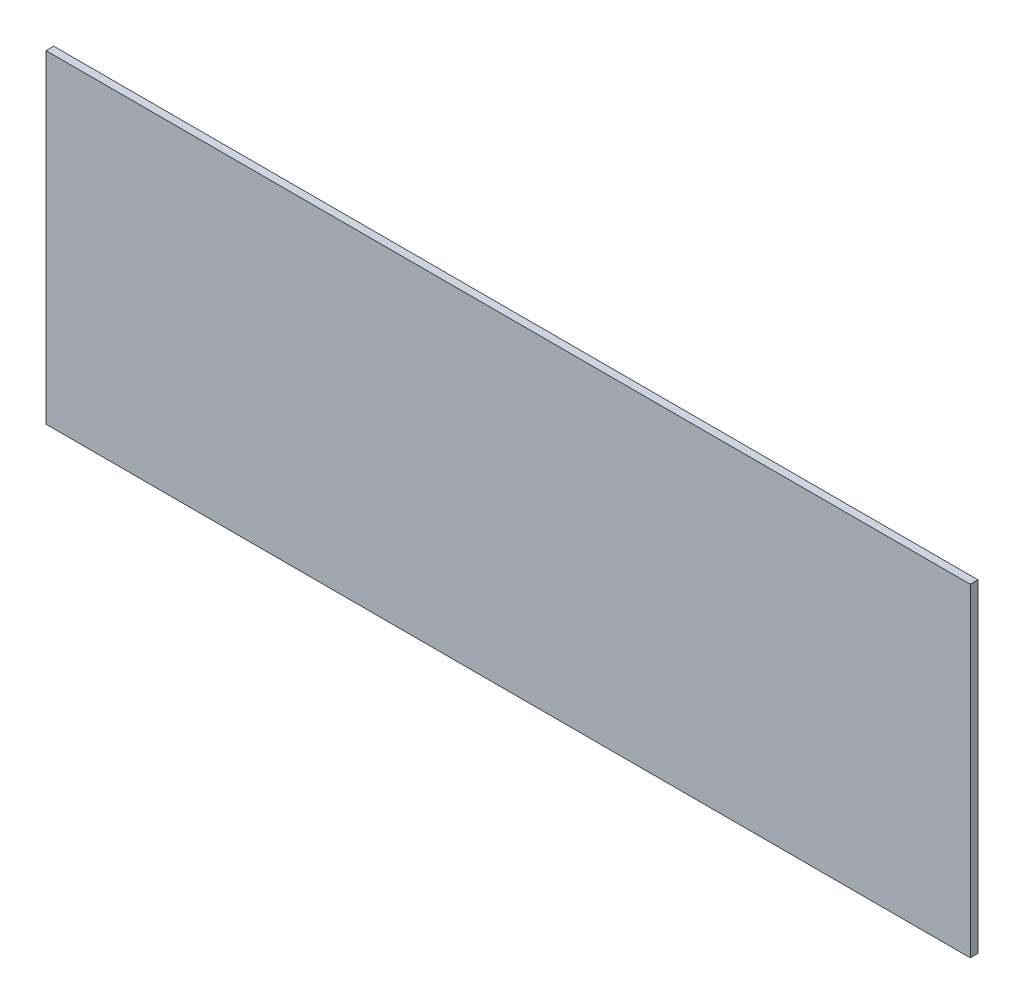
SolidWorks part; units mm, degrees
ref_plane "Front Plane" through (0, 0, 0) normal (0, 0, 1) x (1, 0, 0)
ref_plane "Top Plane" through (0, 0, 0) normal (0, 1, 0) x (1, 0, 0)
ref_plane "Right Plane" through (0, 0, 0) normal (1, 0, 0) x (0, 0, -1)
sketch "Sketch1" plane through (0, 0, 0) normal (0, 0, 1) x (1, 0, 0)
  line L1 (-190.5, -66.675) -> (190.5, -66.675)
  line L2 (-190.5, -66.675) -> (-190.5, 66.675)
  line L3 (-190.5, 66.675) -> (190.5, 66.675)
  line L4 (190.5, -66.675) -> (190.5, 66.675)
  line L5 (-190.5, -66.675) -> (190.5, 66.675) construction
  line L6 (-190.5, 66.675) -> (190.5, -66.675) construction
  point P0 (0, 0)
  dimension "D1" = 381
  dimension "D2" = 133.35
extrude "Boss-Extrude1" add sketch "Sketch1" along normal blind 3.175
